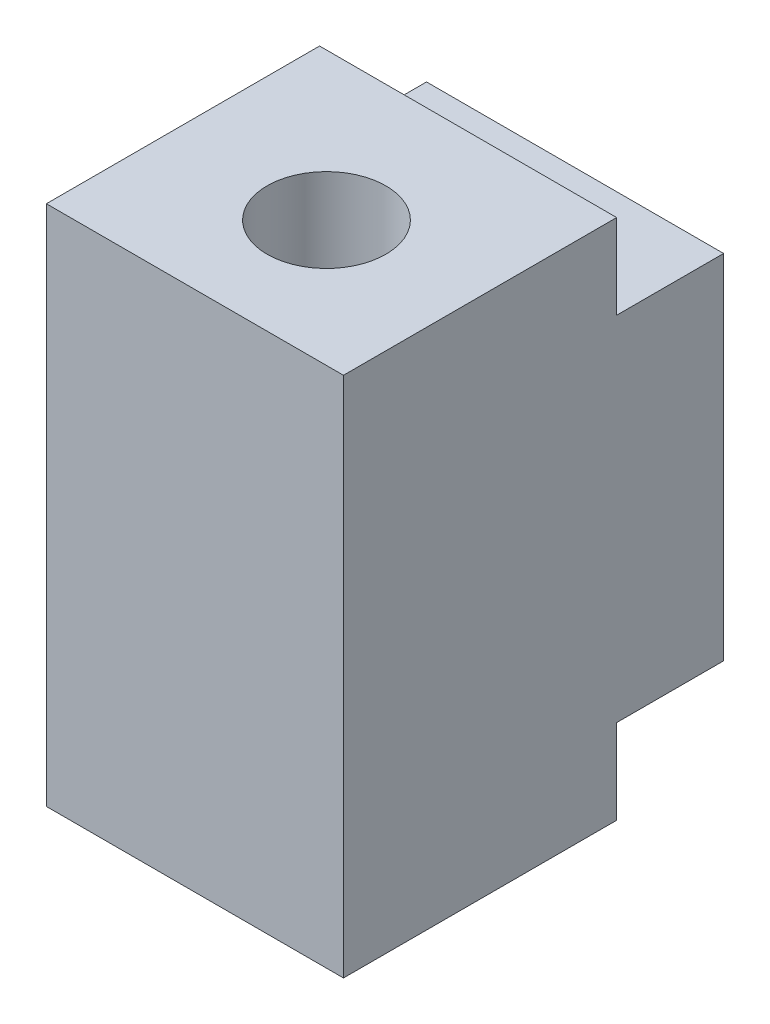
SolidWorks part; units mm, degrees
ref_plane "Front Plane" through (0, 0, 0) normal (0, 0, 1) x (1, 0, 0)
ref_plane "Top Plane" through (0, 0, 0) normal (0, 1, 0) x (1, 0, 0)
ref_plane "Right Plane" through (0, 0, 0) normal (1, 0, 0) x (0, 0, -1)
sketch "Sketch1" plane through (0, 0, 0) normal (0, 0, 1) x (1, 0, 0)
  line L0 (11.5, -14.2) -> (11.5, 14.2) construction
  line L1 (-12.4057, -14.1874) -> (11.5, -14.1874)
  line L2 (-12.4057, -14.1874) -> (-12.4057, 14.2)
  line L3 (-12.4057, 14.2) -> (11.5, 14.2)
  line L4 (11.5, -14.1874) -> (11.5, 14.2)
extrude "Boss-Extrude1" add sketch "Sketch1" along normal blind 30
sketch "Sketch3" plane through (11.5, 0, 0) normal (1, 0, 0) x (0, 0, -1)
  line L0 (-8.6059, 0.0063) -> (-30.5867, 0.0063) construction
  line L1 (-30.5867, 21.0063) -> (-8.6059, 21.0063)
  line L2 (-30.5867, 21.0063) -> (-30.5867, -20.9937)
  line L3 (-30.5867, -20.9937) -> (-8.6059, -20.9937)
  line L4 (-8.6059, 21.0063) -> (-8.6059, -20.9937)
  line L5 (-30, 0.0063) -> (-6.1107, 0.0063) construction
  line L6 (-30, -14.1874) -> (-30, 14.2) construction
  dimension "D1" = 42
extrude "Boss-Extrude2" add sketch "Sketch3" against normal through all
sketch "Sketch2" plane through (0, 21.0063, 0) normal (0, 1, 0) x (1, 0, 0)
  circle A0 centre (0, -20.4542) radius 4.7759
extrude "Cut-Extrude1" cut sketch "Sketch2" against normal through all
